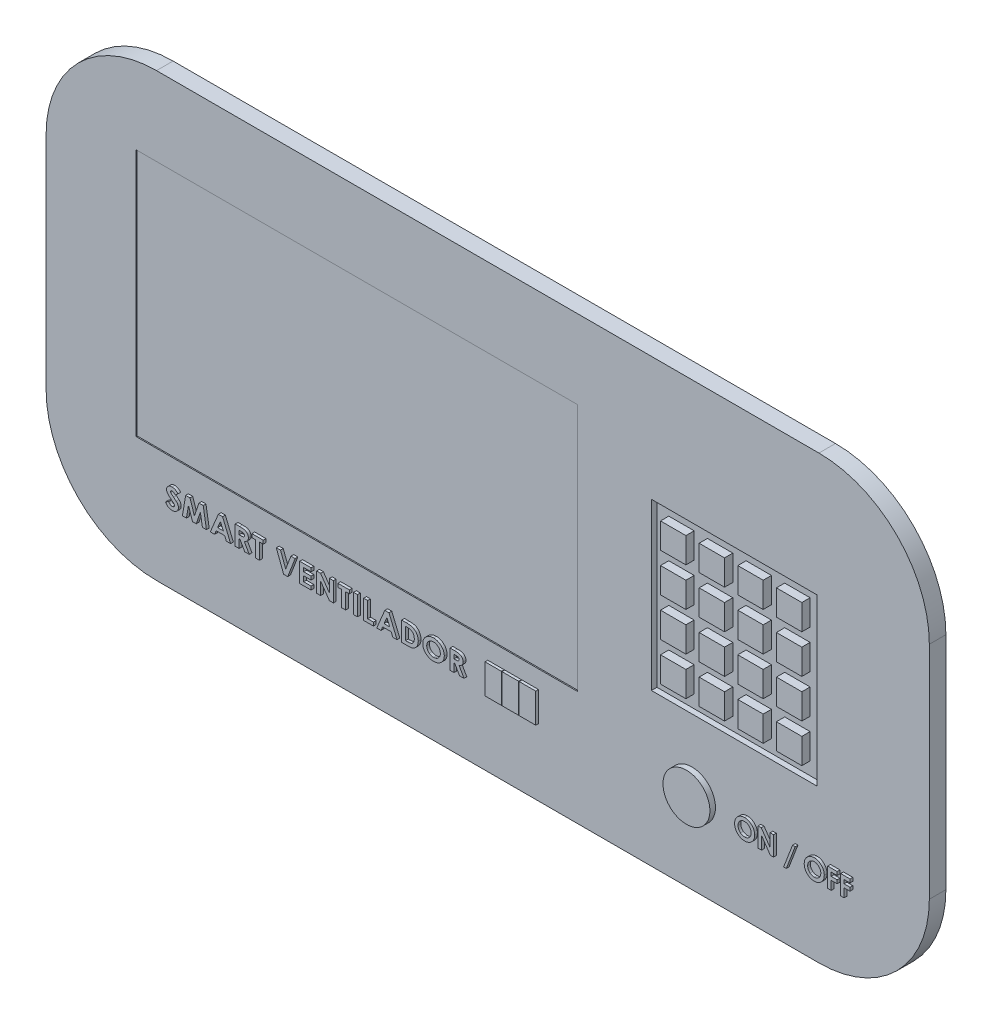
SolidWorks part; units mm, degrees
ref_plane "Alzado" through (0, 0, 0) normal (0, 0, 1) x (1, 0, 0)
ref_plane "Planta" through (0, 0, 0) normal (0, 1, 0) x (1, 0, 0)
ref_plane "Vista lateral" through (0, 0, 0) normal (1, 0, 0) x (0, 0, -1)
sketch "Croquis1" plane through (0, 0, 0) normal (0, 0, 1) x (1, 0, 0)
  line L1 (-60, 40) -> (60, 40)
  line L2 (-80, 20) -> (-80, -20)
  line L3 (-60, -40) -> (60, -40)
  line L4 (80, 20) -> (80, -20)
  line L5 (-80, 40) -> (80, -40) construction
  line L6 (-80, -40) -> (80, 40) construction
  arc A0 (-80, -20) -> (-60, -40) centre (-60, -20) ccw
  arc A1 (60, -40) -> (80, -20) centre (60, -20) ccw
  arc A2 (60, 40) -> (80, 20) centre (60, 20) cw
  arc A3 (-60, 40) -> (-80, 20) centre (-60, 20) ccw
  point P0 (0, 0)
  dimension "D3" = 20
  dimension "D1" = 80
  dimension "D2" = 160
extrude "Saliente-Extruir1" add sketch "Croquis1" along normal blind 3
sketch "Croquis2" plane through (0, 0, 3) normal (0, 0, 1) x (1, 0, 0)
  line L0 (-58, -27) -> (-3, -27) construction
  text T0 "<b>SMART VENTILADOR</b>" font "Century Gothic" height 3.5
  dimension "D1" = 27
  dimension "D2" = 55
  dimension "D3" = 3
extrude "Saliente-Extruir2" add sketch "Croquis2" along normal blind 0.5
sketch "Croquis3" plane through (0, 0, 3) normal (0, 0, 1) x (1, 0, 0)
  line L0 (45, -27) -> (68.36, -27) construction
  text T0 "<b>ON / OFF</b>"
  dimension "D1" = 45
extrude "Saliente-Extruir3" add sketch "Croquis3" along normal blind 0.5
sketch "Croquis4" plane through (0, 0, 3) normal (0, 0, 1) x (1, 0, 0)
  line L0 (3.1, -22.5) -> (6.1, -22.5)
  line L1 (0, -22.5) -> (3, -22.5)
  line L2 (0, -22.5) -> (0, -27.85)
  line L3 (0, -27.85) -> (3, -27.85)
  line L4 (3, -22.5) -> (3, -27.85)
  line L5 (0, -22.5) -> (3, -27.85) construction
  line L6 (0, -27.85) -> (3, -22.5) construction
  line L7 (3.1, -22.5) -> (3.1, -27.85)
  line L8 (6.1, -22.5) -> (6.1, -27.85)
  line L9 (3.1, -27.85) -> (6.1, -27.85)
  line L10 (6.2, -22.5) -> (9.2, -22.5)
  line L11 (6.2, -22.5) -> (6.2, -27.85)
  line L12 (9.2, -22.5) -> (9.2, -27.85)
  line L13 (6.2, -27.85) -> (9.2, -27.85)
  point P0 (1.5, -25.175)
  dimension "D1" = 3
  dimension "D2" = 5.35
  dimension "D3" = 22.5
  dimension "D4" = 3
  dimension "D6" = 3.1
  dimension "D5" = 3
extrude "Saliente-Extruir4" add sketch "Croquis4" along normal blind 0.5
sketch "Croquis5" plane through (0, 0, 3) normal (0, 0, 1) x (1, 0, 0)
  line L1 (-63.7226, 25.7343) -> (16.2774, 25.7343)
  line L2 (-63.7226, 25.7343) -> (-63.7226, -19.2657)
  line L3 (-63.7226, -19.2657) -> (16.2774, -19.2657)
  line L4 (16.2774, 25.7343) -> (16.2774, -19.2657)
  line L5 (-63.7226, 25.7343) -> (16.2774, -19.2657) construction
  line L6 (-63.7226, -19.2657) -> (16.2774, 25.7343) construction
  point P0 (-23.7226, 3.2343)
  dimension "D1" = 80
  dimension "D2" = 45
  dimension "D3" = 23.7226
  dimension "D4" = 3.2343
extrude "Cortar-Extruir1" cut sketch "Croquis5" against normal blind 0.2
sketch "Croquis6" plane through (0, 0, 3) normal (0, 0, 1) x (1, 0, 0)
  circle A0 centre (37, -25) radius 4.25
  dimension "D1" = 8.5
  dimension "D2" = 37
  dimension "D3" = 25
extrude "Saliente-Extruir5" add sketch "Croquis6" along normal blind 1 contours A0
sketch "Croquis7" plane through (0, 0, 3) normal (0, 0, 1) x (1, 0, 0)
  line L1 (29.6564, 17.5756) -> (59.6564, 17.5756)
  line L2 (29.6564, 17.5756) -> (29.6564, -12.4244)
  line L3 (29.6564, -12.4244) -> (59.6564, -12.4244)
  line L4 (59.6564, 17.5756) -> (59.6564, -12.4244)
  line L5 (29.6564, 17.5756) -> (59.6564, -12.4244) construction
  line L6 (29.6564, -12.4244) -> (59.6564, 17.5756) construction
  point P0 (44.6564, 2.5756)
  dimension "D1" = 30
  dimension "D2" = 30
  dimension "D3" = 17.5756
  dimension "D4" = 29.6564
extrude "Cortar-Extruir2" cut sketch "Croquis7" against normal blind 1
sketch "Croquis8" plane through (0, 0, 2) normal (0, 0, 1) x (1, 0, 0)
  line L0 (38.8, 15.5) -> (38.8, 10.9)
  line L5 (31.8, 15.5) -> (36.4, 15.5)
  line L6 (31.8, 15.5) -> (31.8, 10.9)
  line L7 (31.8, 10.9) -> (36.4, 10.9)
  line L8 (36.4, 15.5) -> (36.4, 10.9)
  line L9 (31.8, 15.5) -> (36.4, 10.9) construction
  line L10 (31.8, 10.9) -> (36.4, 15.5) construction
  line L11 (38.8, 15.5) -> (43.4, 15.5)
  line L12 (43.4, 15.5) -> (43.4, 10.9)
  line L13 (38.8, 10.9) -> (43.4, 10.9)
  line L14 (45.8, 15.5) -> (45.8, 10.9)
  line L15 (45.8, 15.5) -> (50.4, 15.5)
  line L16 (50.4, 15.5) -> (50.4, 10.9)
  line L17 (45.8, 10.9) -> (50.4, 10.9)
  line L18 (52.8, 15.5) -> (52.8, 10.9)
  line L19 (52.8, 15.5) -> (57.4, 15.5)
  line L20 (57.4, 15.5) -> (57.4, 10.9)
  line L21 (52.8, 10.9) -> (57.4, 10.9)
  line L22 (38.8, 8.5) -> (38.8, 3.9)
  line L23 (38.8, 8.5) -> (43.4, 8.5)
  line L24 (43.4, 8.5) -> (43.4, 3.9)
  line L25 (38.8, 3.9) -> (43.4, 3.9)
  line L26 (45.8, 8.5) -> (45.8, 3.9)
  line L27 (45.8, 8.5) -> (50.4, 8.5)
  line L28 (50.4, 8.5) -> (50.4, 3.9)
  line L29 (45.8, 3.9) -> (50.4, 3.9)
  line L30 (52.8, 8.5) -> (52.8, 3.9)
  line L31 (52.8, 8.5) -> (57.4, 8.5)
  line L32 (57.4, 8.5) -> (57.4, 3.9)
  line L33 (52.8, 3.9) -> (57.4, 3.9)
  line L34 (38.8, 1.5) -> (38.8, -3.1)
  line L35 (38.8, 1.5) -> (43.4, 1.5)
  line L36 (43.4, 1.5) -> (43.4, -3.1)
  line L37 (38.8, -3.1) -> (43.4, -3.1)
  line L38 (45.8, 1.5) -> (45.8, -3.1)
  line L39 (45.8, 1.5) -> (50.4, 1.5)
  line L40 (50.4, 1.5) -> (50.4, -3.1)
  line L41 (45.8, -3.1) -> (50.4, -3.1)
  line L42 (52.8, 1.5) -> (52.8, -3.1)
  line L43 (52.8, 1.5) -> (57.4, 1.5)
  line L44 (57.4, 1.5) -> (57.4, -3.1)
  line L45 (52.8, -3.1) -> (57.4, -3.1)
  line L46 (38.8, -5.5) -> (38.8, -10.1)
  line L47 (38.8, -5.5) -> (43.4, -5.5)
  line L48 (43.4, -5.5) -> (43.4, -10.1)
  line L49 (38.8, -10.1) -> (43.4, -10.1)
  line L50 (45.8, -5.5) -> (45.8, -10.1)
  line L51 (45.8, -5.5) -> (50.4, -5.5)
  line L52 (50.4, -5.5) -> (50.4, -10.1)
  line L53 (45.8, -10.1) -> (50.4, -10.1)
  line L54 (52.8, -5.5) -> (52.8, -10.1)
  line L55 (52.8, -5.5) -> (57.4, -5.5)
  line L56 (57.4, -5.5) -> (57.4, -10.1)
  line L57 (52.8, -10.1) -> (57.4, -10.1)
  line L58 (31.8, 8.5) -> (31.8, 3.9)
  line L59 (31.8, 8.5) -> (36.4, 8.5)
  line L60 (36.4, 8.5) -> (36.4, 3.9)
  line L61 (31.8, 3.9) -> (36.4, 3.9)
  line L62 (31.8, 1.5) -> (31.8, -3.1)
  line L63 (31.8, 1.5) -> (36.4, 1.5)
  line L64 (36.4, 1.5) -> (36.4, -3.1)
  line L65 (31.8, -3.1) -> (36.4, -3.1)
  line L66 (31.8, -5.5) -> (31.8, -10.1)
  line L67 (31.8, -5.5) -> (36.4, -5.5)
  line L68 (36.4, -5.5) -> (36.4, -10.1)
  line L69 (31.8, -10.1) -> (36.4, -10.1)
  point P0 (34.1, 13.2)
  dimension "D1" = 4.6
  dimension "D2" = 15.5
  dimension "D3" = 31.8
  dimension "D6" = 7
  dimension "D7" = 7
  dimension "D8" = 4.6
  dimension "D4" = 4
  dimension "D5" = 4
extrude "Saliente-Extruir6" add sketch "Croquis8" along normal blind 1.5
